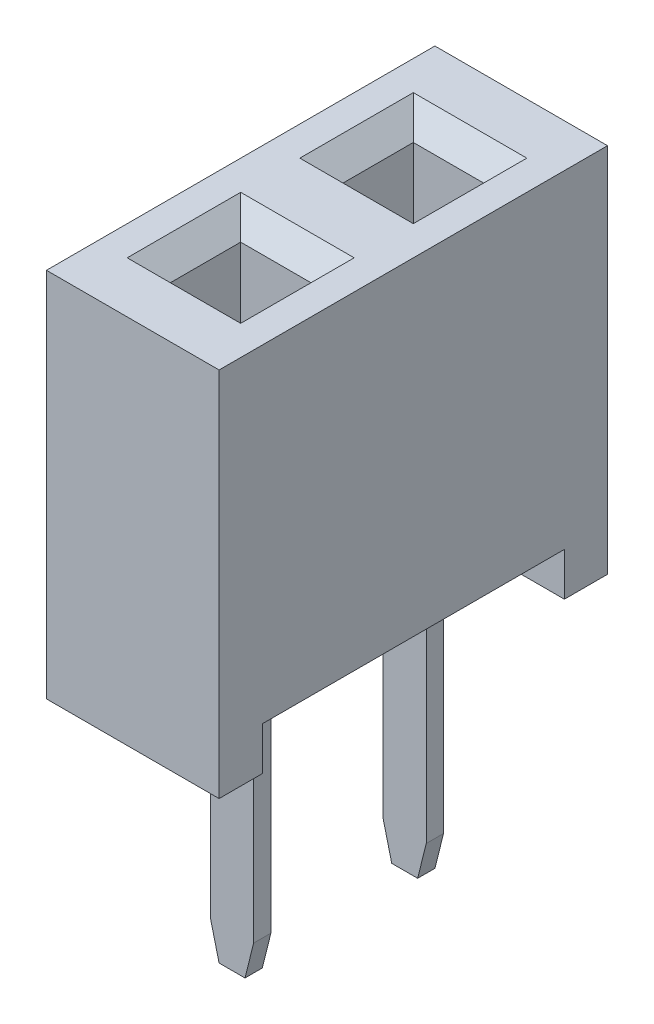
SolidWorks part; units mm, degrees
ref_plane "Front" through (0, 0, 0) normal (0, 0, 1) x (1, 0, 0)
ref_plane "Top" through (0, 0, 0) normal (0, 1, 0) x (1, 0, 0)
ref_plane "Right" through (0, 0, 0) normal (1, 0, 0) x (0, 0, -1)
sketch "草图1" plane through (0, 0, 0) normal (1, 0, 0) x (0, 0, -1)
  line L0 (-2.25, 0) -> (2.25, 0)
  line L1 (2.25, 0) -> (2.25, -4.3)
  line L2 (2.25, -4.3) -> (1.75, -4.3)
  line L3 (1.75, -4.3) -> (1.75, -3.8)
  line L4 (1.75, -3.8) -> (-1.75, -3.8)
  line L5 (0, -3.8) -> (0, 0) construction
  line L6 (-1.75, -4.3) -> (-1.75, -3.8)
  line L7 (-2.25, -4.3) -> (-1.75, -4.3)
  line L8 (-2.25, 0) -> (-2.25, -4.3)
  dimension "D1" = 4.5
  dimension "D2" = 4.3
  dimension "D3" = 0.5
  dimension "D4" = 0.5
extrude "凸台-拉伸1" add sketch "草图1" along normal mid plane 2
sketch "草图3" plane through (0, 0, 0) normal (0, 1, 0) x (1, 0, 0)
  line L0 (0, 2.25) -> (0, -2.25) construction
  line L1 (1, 2.25) -> (-1, 2.25) construction
  line L2 (1, -2.25) -> (-1, -2.25) construction
  line L3 (0, 0) -> (1, 0) construction
  line L4 (0.7333, 0.2667) -> (-0.7333, 0.2667)
  line L5 (0.7333, 0.2667) -> (0.7333, 1.7333)
  line L6 (0.7333, 1.7333) -> (-0.7333, 1.7333)
  line L7 (-0.7333, 0.2667) -> (-0.7333, 1.7333)
  line L8 (1, 0) -> (-0.7333, 1.7333) construction
  line L9 (0.7333, 1.7333) -> (-0.7333, 0.2667) construction
  line L10 (1, 2.25) -> (1, -2.25) construction
  line L12 (0.4074, 0.5926) -> (-0.4074, 0.5926)
  line L13 (0.4074, 0.5926) -> (0.4074, 1.4074)
  line L14 (0.4074, 1.4074) -> (-0.4074, 1.4074)
  line L15 (-0.4074, 0.5926) -> (-0.4074, 1.4074)
  line L16 (0.4074, 0.5926) -> (-0.4074, 1.4074) construction
  line L17 (0.4074, 1.4074) -> (-0.4074, 0.5926) construction
  point P6 (0, 1)
  point P16 (0, 1)
  point P21 (-0.4683, 1.4683)
  point P22 (-0.4074, 1.4074)
  dimension "D1" = 1
  dimension "D2" = 0.5334
  dimension "D3" = 0.5167
  dimension "D4" = 1.4666
extrude "切除-拉伸1" cut sketch "草图3" against normal blind 3.5 contours L15 L12 L13 L14
chamfer "倒角1" distance 0.25 angle 45 3 edges at (0, 0, -0.5926) (0.4074, 0, -1) (0, 0, -1.4074)
mirror "镜向1" about plane through (0, 0, 0) normal (0, 0, 1) of "倒角1", "切除-拉伸1"
sketch "草图4" plane through (0, 0, 0) normal (1, 0, 0) x (0, 0, -1)
  line L0 (1.563, -3.8) -> (1.1, -4.0888)
  line L1 (-1.75, -3.8) -> (1.75, -3.8) construction
  line L2 (1.1, -4.0888) -> (1.1, -7.1)
  line L3 (1.75, -4.3) -> (2.25, -4.3) construction
  line L4 (1.1851, -3.8) -> (0.9, -3.9778)
  line L5 (0.9, -3.9778) -> (0.9, -7.1)
  line L6 (0.9, -7.1) -> (1.1, -7.1)
  line L7 (1.563, -3.8) -> (1.1851, -3.8)
  line L9 (1.4571, -3.6303) -> (0.9, -3.9778) construction
  point P10 (0, -3.8)
  point P12 (1, -7.1)
  dimension "D1" = 2.8
  dimension "D3" = 1
  dimension "D2" = 0.2
extrude "凸台-拉伸2" add sketch "草图4" along normal blind 0.25
chamfer "倒角2" distance 0.1 distance2 0.4 1 edges at (0.25, -7.1, -1)
sketch "草图5" plane through (0, 0, 0) normal (0, 1, 0) x (1, 0, 0)
  line L0 (1, 2.25) -> (-1, 2.25) construction
  line L1 (0, 2.25) -> (-1, 2.25)
  line L2 (0, 2.25) -> (0, 0)
  line L3 (1, -2.25) -> (-1, -2.25)
  line L4 (-1, 2.25) -> (-1, -2.25)
  line L5 (0, 0) -> (1, 0)
  line L6 (1, 2.25) -> (1, -2.25) construction
  line L7 (1, 0) -> (1, -2.25)
extrude "切除-拉伸2" cut sketch "草图5" against normal through all
mirror "镜向3" about plane through (0, 0, 0) normal (1, 0, 0) of bodies 106
mirror "镜向4" about plane through (0, -7.1, 0) normal (0, 0, -1) of bodies 107
